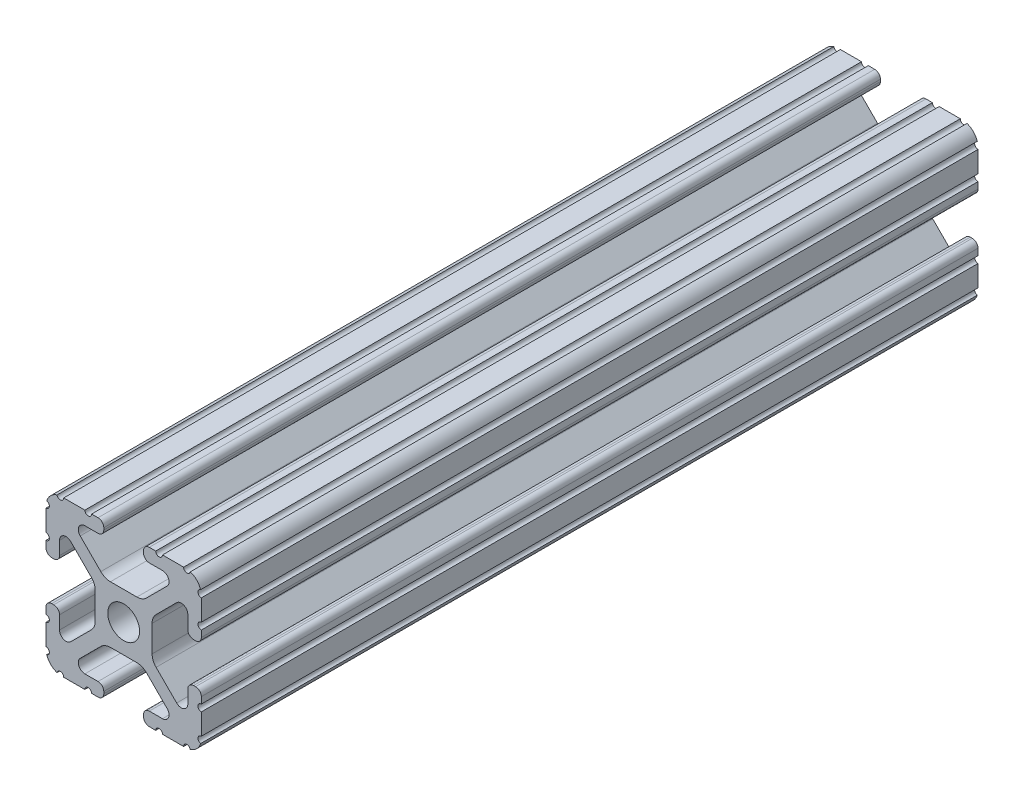
SolidWorks part; units mm, degrees
ref_plane "Front Plane" through (0, 0, 0) normal (0, 0, 1) x (1, 0, 0)
ref_plane "Top Plane" through (0, 0, 0) normal (0, 1, 0) x (1, 0, 0)
ref_plane "Right Plane" through (0, 0, 0) normal (1, 0, 0) x (0, 0, -1)
sketch "Sketch2" plane through (0, 0, 0) normal (0, 0, 1) x (1, 0, 0)
  line L0 (0, 12.7) -> (0, -12.7) construction
  line L1 (-12.7, 0) -> (12.7, 0) construction
  line L2 (3.2512, -12.7) -> (12.7, -12.7)
  line L3 (12.7, -12.7) -> (12.7, -3.2512)
  line L4 (3.2512, -12.7) -> (3.2512, -10.4902)
  line L5 (3.2512, -10.4902) -> (8.9276, -10.4902)
  line L6 (8.9276, -10.4902) -> (3.0856, -4.6482)
  line L7 (0, 0) -> (12.7, -12.7) construction
  line L8 (12.7, -3.2512) -> (10.4902, -3.2512)
  line L9 (10.4902, -3.2512) -> (10.4902, -8.9276)
  line L10 (10.4902, -8.9276) -> (4.6482, -3.0856)
  circle A0 centre (0, 0) radius 2.6035
  arc A1 (6.3485, -10.4902) -> (7.1039, -8.6665) centre (6.3485, -9.4219) ccw construction
  point P8 (0, -4.6482)
  dimension "Center Hole Diameter" = 5.207
  dimension "Rail Height" = 25.4
  dimension "Rail Width" = 25.4
  dimension "T-Slot Width" = 6.5024
  dimension "Slot Inner Width" = 14.8336
  dimension "Thickness" = 2.2098
  dimension "Slot Depth" = 5.842
  dimension "D1" = 2.2098
sketch "Sketch3" plane through (0, 0, 0) normal (1, 0, 0) x (0, 0, -1)
  line L0 (-63.5, -12.7) -> (63.5, -12.7) construction
  line L1 (-38.1, 0) -> (38.1, 0) construction
  line L3 (63.5, 0) -> (-63.5, 0) construction
sketch "Sketch4" plane through (0, 0, 0) normal (0, 0, 1) x (1, 0, 0)
  line L0 (4.1904, -12.7) -> (10.1173, -12.7)
  line L1 (3.2512, -12.7) -> (12.7, -12.7) construction
  line L2 (3.2512, -12.7) -> (3.2512, -10.4902) construction
  line L3 (3.2512, -10.4902) -> (8.9276, -10.4902) construction
  line L4 (3.2512, -11.4294) -> (3.2512, -11.7608)
  line L5 (4.1904, -10.4902) -> (6.3485, -10.4902)
  line L6 (0, -4.6482) -> (2.164, -4.6482)
  line L7 (8.9276, -10.4902) -> (3.0856, -4.6482) construction
  line L8 (3.7373, -5.2999) -> (7.1039, -8.6665)
  line L9 (12.7, -12.7) -> (12.7, -3.2512) construction
  line L10 (10.4902, -8.9276) -> (4.6482, -3.0856) construction
  line L11 (10.4902, -3.2512) -> (10.4902, -8.9276) construction
  line L12 (10.4902, -6.3485) -> (10.4902, -4.1904)
  line L13 (12.7, -3.2512) -> (10.4902, -3.2512) construction
  line L14 (11.4294, -3.2512) -> (11.7608, -3.2512)
  line L15 (12.7, -4.1904) -> (12.7, -10.1173)
  line L16 (8.6665, -7.1039) -> (5.2999, -3.7373)
  line L17 (4.6482, 0) -> (4.6482, -2.164)
  line L18 (-12.7, 0) -> (12.7, 0) construction
  line L19 (0, -4.6482) -> (0, -2.6035)
  line L20 (0, 12.7) -> (0, -12.7) construction
  line L21 (4.6482, 0) -> (2.6035, 0)
  arc A0 (3.2512, -11.7608) -> (4.1904, -12.7) centre (4.1904, -11.7608) ccw
  arc A2 (3.2512, -11.4294) -> (4.1904, -10.4902) centre (4.1904, -11.4294) cw
  arc A3 (6.3485, -10.4902) -> (7.1039, -8.6665) centre (6.3485, -9.4219) ccw
  arc A4 (2.164, -4.6482) -> (3.7373, -5.2999) centre (2.164, -6.8732) cw
  arc A5 (10.1173, -12.7) -> (12.7, -10.1173) centre (10.1173, -10.1173) ccw
  arc A6 (8.6665, -7.1039) -> (10.4902, -6.3485) centre (9.4219, -6.3485) ccw
  arc A7 (10.4902, -4.1904) -> (11.4294, -3.2512) centre (11.4294, -4.1904) cw
  arc A8 (11.7608, -3.2512) -> (12.7, -4.1904) centre (11.7608, -4.1904) cw
  arc A9 (5.2999, -3.7373) -> (4.6482, -2.164) centre (6.8732, -2.164) cw
  circle A10 centre (0, 0) radius 2.6035 construction
  arc A11 (0, -2.6035) -> (2.6035, 0) centre (0, 0) ccw
  dimension "D1" = 2.5827
  dimension "D2" = 2.225
  dimension "D3" = 0.9392
extrude "Boss-Extrude1" add sketch "Sketch4" along normal up to vertex (63.5 mm away) from vertex at -63.5 starting at point (0, -12.7, -63.5)
sketch "Sketch5" plane through (0, 0, 0) normal (0, 0, 1) x (1, 0, 0)
  line L0 (3.2512, -12.7) -> (12.7, -12.7) construction
  line L1 (4.1904, -10.4902) -> (6.3485, -10.4902) construction
  line L3 (0, 0) -> (12.7, -12.7) construction
  line L4 (6.3485, -10.4902) -> (6.3485, -12.7) construction
  line L5 (8.9276, -10.4902) -> (3.0856, -4.6482) construction
  circle A0 centre (10.3562, -12.7) radius 0.5524
  circle A1 centre (5.796, -12.7) radius 0.5524
  circle A2 centre (12.7, -10.3562) radius 0.5524
  circle A3 centre (12.7, -5.796) radius 0.5524
  point P10 (5.2694, -10.4902)
  point P12 (9.4219, -6.3485)
  dimension "D1" = 1.1049
extrude "Cut-Extrude1" cut sketch "Sketch5" against normal through all both and the other way through all
mirror "Mirror1" about plane through (0, 0, 0) normal (1, 0, 0) of bodies 137 134
mirror "Mirror2" about plane through (0, 0, 0) normal (0, 1, 0) of bodies 135
equation "\"D1@Sketch2\"=\"Thickness@Sketch2\""
equation "\"D2@Sketch4\"=\"Slot Inner Width@Sketch2\"*0.15"
equation "\"D1@Sketch4\"=\"D3@Sketch4\"*2.75"
equation "\"D3@Sketch4\"=\"Thickness@Sketch2\"*0.425"
equation "\"D1@Sketch5\"=\"Thickness@Sketch2\"*0.5"
equation "\"D1@Boss-Extrude1\"=\"Length@Sketch3\""
